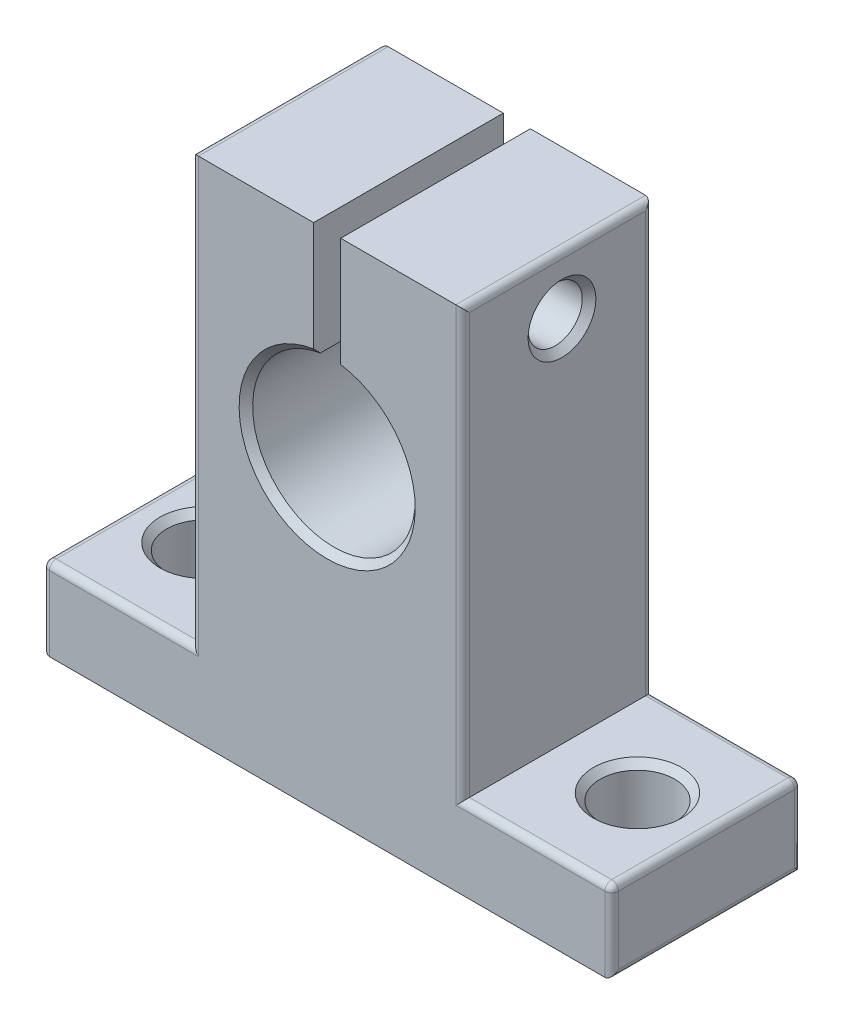
SolidWorks part; units mm, degrees
material "1060 Alloy"
ref_plane "Front Plane" through (0, 0, 0) normal (0, 0, 1) x (1, 0, 0)
ref_plane "Top Plane" through (0, 0, 0) normal (0, 1, 0) x (1, 0, 0)
ref_plane "Right Plane" through (0, 0, 0) normal (1, 0, 0) x (0, 0, -1)
sketch "Sketch1" plane through (0, 0, 0) normal (0, 0, 1) x (1, 0, 0)
  line L0 (0, 0) -> (-50000, 0) construction
  line L1 (0, 0) -> (0, 50000) construction
  line L2 (-21, -3) -> (-21, 3)
  line L3 (-21, 3) -> (-10, 3)
  line L4 (-10, 3) -> (-10, 34.5)
  line L5 (-10, 34.5) -> (-1, 34.5)
  line L6 (10, 34.5) -> (10, 3)
  line L7 (10, 3) -> (21, 3)
  line L8 (21, 3) -> (21, -3)
  line L9 (21, -3) -> (-21, -3)
  line L10 (16, -3) -> (16, 3) construction
  line L11 (-16, -3) -> (-16, 3) construction
  line L12 (-1, 34.5) -> (-1, 25.9161)
  line L13 (1, 34.5) -> (1, 25.9161)
  line L14 (1, 34.5) -> (10, 34.5)
  arc A0 (-1, 25.9161) -> (1, 25.9161) centre (0, 20) ccw
  point P8 (-21, 0)
  point P15 (0, -3)
  point P21 (16, 0)
  dimension "Shaft Diameter" = 12
  dimension "W" = 42
  dimension "P" = 20
  dimension "F" = 37.5
  dimension "G" = 6
  dimension "B" = 32
  dimension "D1" = 2
  dimension "h" = 23
extrude "Boss-Extrude1" add sketch "Sketch1" along normal mid plane 14
sketch "Sketch2" plane through (0, 3, 0) normal (0, 1, 0) x (1, 0, 0)
  line L0 (0, 0) -> (50000, 0) construction
  line L1 (0.3141, 0) -> (-49999.6859, 0) construction
  line L2 (-0.0955, 2.4842) -> (-0.0955, 50002.4842) construction
  circle A0 centre (15.9045, 0) radius 2.75
  circle A1 centre (-16.0955, 0) radius 2.75
  dimension "B" = 32
  dimension "S" = 5.5
extrude "Cut-Extrude1" cut sketch "Sketch2" against normal through all
sketch "Sketch5" plane through (-1, 0, 0) normal (1, 0, 0) x (0, 0, -1)
  line L0 (-7, 30.208) -> (7, 30.208) construction
  line L1 (7, 25.9161) -> (7, 34.5) construction
  line L2 (0, 34.5) -> (0, 25.9161) construction
  line L3 (-7, 34.5) -> (7, 34.5) construction
  line L4 (-7, 25.9161) -> (7, 25.9161) construction
  line L5 (-7, 25.9161) -> (-7, 34.5) construction
  circle A0 centre (0.3307, 30.208) radius 2
  dimension "Clamping bold" = 4
extrude "Cut-Extrude2" cut sketch "Sketch5" against normal through all both and the other way through all
chamfer "Chamfer2" distance 0.5 angle 45 6 edges at (0, 14, -7) (0, 14, 7) (-10, 30.208, -2.3307) (-13.3455, 3, 0) (10, 30.208, 1.6693) (13.1545, 3, 0)
fillet "Fillet2" radius 0.5 18 edges at (21, -3, 0) (21, 0, 7) (21, 3, 0) (21, 0, -7) (-21, 3, 0) (-21, 0, 7) (-21, -3, 0) (-21, 0, -7) (-15.5, 3, -7) (-15.5, 3, 7) (-10, 18.75, 7) (-10, 34.5, 0) (-10, 18.75, -7) (10, 18.75, -7) (10, 18.75, 7) (15.5, 3, 7) (15.5, 3, -7) (10, 34.5, 0)
ref_plane "Plane1" through (15.9, 0, 0) normal (1, 0, 0) x (0, 0, -1)
ref_plane "Plane2" through (-15.9, 0, 0) normal (-1, 0, 0) x (0, 0, 1)
equation "\"W\"= \"W@Sketch1\"'Width"
equation "\"B\"= \"B@Sketch1\"'between hold"
equation "\"F\"= \"F@Sketch1\"'Hight"
equation "\"P\"= \"P@Sketch1\""
equation "\"G\"= \"G@Sketch1\""
equation "\"Shaft diameter\"= \"Shaft Diameter@Sketch1\""
equation "\"S\"= 5.5'M5"
equation "\"Clamping bold\"= 4'M4"
equation "\"h\"= \"h@Sketch1\""
